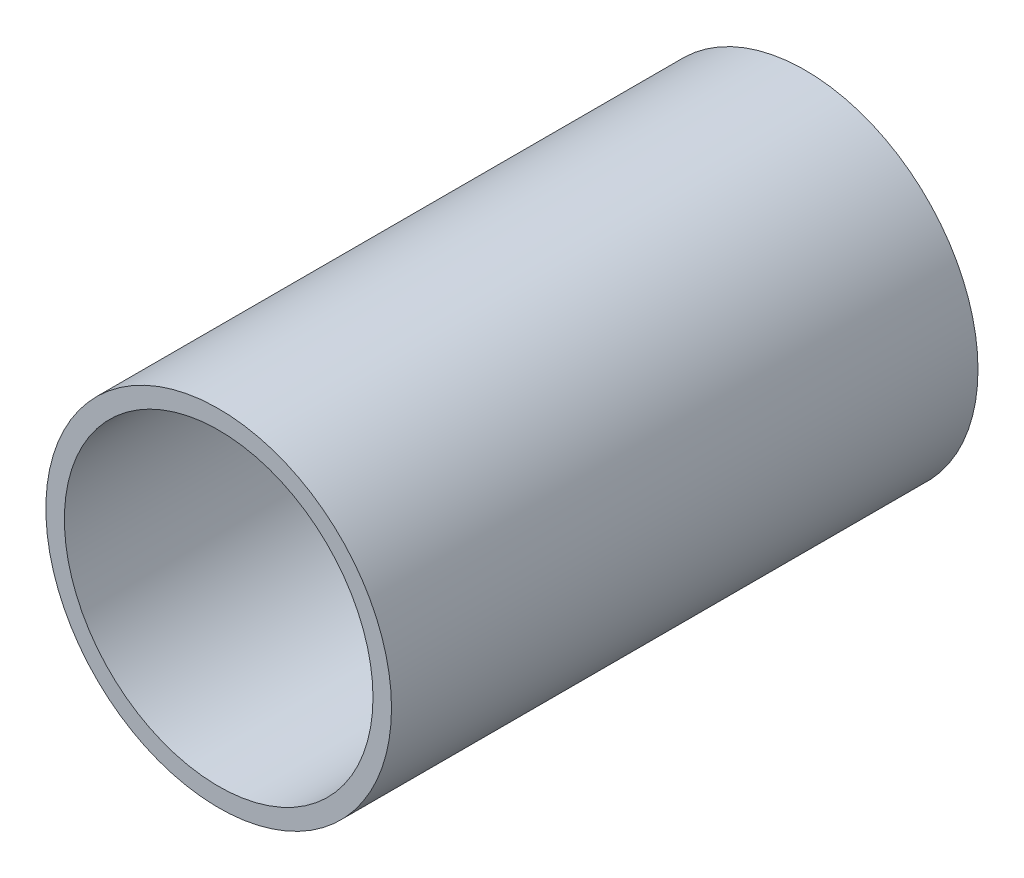
SolidWorks part; units mm, degrees
ref_plane "Plan de face" through (0, 0, 0) normal (0, 0, 1) x (1, 0, 0)
ref_plane "Plan de dessus" through (0, 0, 0) normal (0, 1, 0) x (1, 0, 0)
ref_plane "Plan de droite" through (0, 0, 0) normal (1, 0, 0) x (0, 0, -1)
sketch "Esquisse1" plane through (0, 0, 0) normal (0, 0, 1) x (1, 0, 0)
  circle A0 centre (0, 0) radius 27.9943
  dimension "D1" = 55.9887
extrude "Boss.-Extru.1" add sketch "Esquisse1" along normal blind 95 contours A0
sketch "Esquisse2" plane through (0, 0, 95) normal (0, 0, 1) x (1, 0, 0)
  circle A0 centre (0, 0) radius 24.9943
  circle A1 centre (0, 0) radius 27.9943 construction
  dimension "D1" = 3
extrude "Enlèv. mat.-Extru.1" cut sketch "Esquisse2" against normal blind 80 contours A0
equation "\"taille\"= 3mm"
